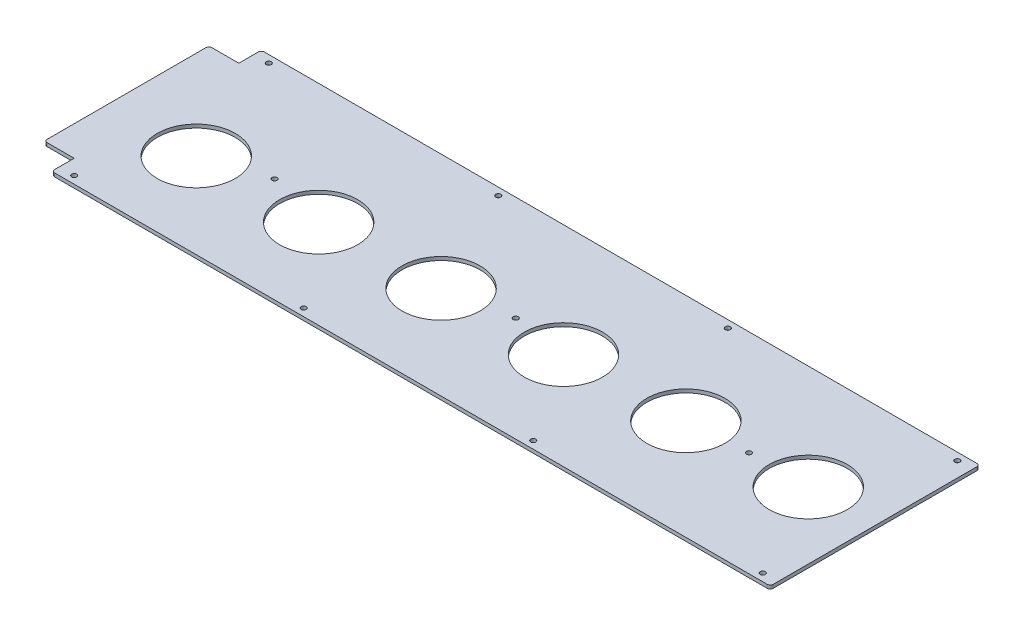
SolidWorks part; units mm, degrees
material "Acrylic (Medium-high impact)"
ref_plane "Front" through (0, 0, 0) normal (0, 0, 1) x (1, 0, 0)
ref_plane "Top" through (0, 0, 0) normal (0, 1, 0) x (1, 0, 0)
ref_plane "Right" through (0, 0, 0) normal (1, 0, 0) x (0, 0, -1)
sketch "Sketch1" plane through (0, 0, 0) normal (0, 1, 0) x (1, 0, 0)
  line L0 (1355.9397, -43.6078) -> (720.9397, -43.6078) construction
  line L5 (1355.9397, 24.9722) -> (1355.9397, -112.1878) construction
  line L6 (720.9397, -112.1878) -> (720.9397, 24.9722) construction
  line L12 (1354.6697, -113.4578) -> (722.2097, -113.4578) construction
  line L13 (746.3397, 45.2922) -> (1355.9397, 45.2922) construction
  line L27 (720.9397, 26.2422) -> (720.9397, -113.4578)
  line L32 (746.3397, -132.5078) -> (1355.9397, -132.5078) construction
  line L44 (1355.9397, 45.2922) -> (1355.9397, -132.5078)
  line L45 (746.3397, 45.2922) -> (1355.9397, -132.5078) construction
  line L50 (746.3397, -132.5078) -> (1355.9397, 45.2922) construction
  line L53 (720.9397, -113.4578) -> (746.3397, -113.4578)
  line L54 (746.3397, -132.5078) -> (746.3397, -113.4578)
  line L58 (720.9397, 26.2422) -> (746.3397, 26.2422)
  line L59 (746.3397, 45.2922) -> (746.3397, 26.2422)
  line L60 (722.2097, 26.2422) -> (1354.6697, 26.2422) construction
  line L61 (1355.9397, -132.5078) -> (746.3397, -132.5078)
  line L62 (1355.9397, 45.2922) -> (746.3397, 45.2922)
  circle A0 centre (1299.3357, -43.6078) radius 33.147
  circle A1 centre (1198.754, -46.8777) radius 33.147
  circle A2 centre (1098.1723, -50.1476) radius 33.147
  circle A3 centre (997.5907, -53.4175) radius 33.147
  circle A4 centre (897.009, -56.6874) radius 33.147
  circle A5 centre (796.4273, -59.9573) radius 33.147
  circle A6 centre (1299.3357, -43.6078) radius 33.02 construction
  point P6 (1051.1397, -43.6078)
  dimension "D3" = 0.127
  dimension "D1" = 177.8
  dimension "D2" = 25.4
extrude "Boss-Extrude1" add sketch "Sketch1" along normal blind 2.9718
hole_wizard "#8 Clearance Hole1" positions "Sketch2" profile "Sketch3" hole size "#8" standard "ANSI Inch" end condition through all
sketch "Sketch2" plane through (0, 2.9718, 0) normal (0, 1, 0) x (1, 0, 0)
  point P0 (759.0397, 38.9422)
  point P3 (759.0397, -126.1578)
  point P6 (953.773, -126.1578)
  point P9 (953.773, 38.9422)
  point P12 (1148.5063, 38.9422)
  point P15 (1148.5063, -126.1578)
  point P18 (1343.2397, -126.1578)
  point P22 (1343.2397, 38.9422)
  point P26 (1249.0183, -43.6078)
  point P29 (1051.1397, -43.6078)
  point P32 (846.4791, -43.6078)
sketch "Sketch3" plane through (759.0397, 2.9718, -38.9422) normal (1, 0, 0) x (0, 0, 1)
  line L0 (0, 0) -> (0, 2.9718)
  line L1 (0, 2.9718) -> (2.1526, 2.9718)
  line L2 (2.1526, 2.9718) -> (2.1526, 0)
  line L5 (2.1526, 0) -> (0, 0)
  line L11 (0, -6.35) -> (0, 107.95) construction
  dimension "Thru Hole Dia." = 4.3053
  dimension "Thru Hole Depth" = 2.9718
fillet "Fillet1" radius 2.54 6 edges at (720.9397, 1.4859, 113.4578) (720.9397, 1.4859, -26.2422) (746.3397, 1.4859, -45.2922) (746.3397, 1.4859, 132.5078) (1355.9397, 1.4859, 132.5078) (1355.9397, 1.4859, -45.2922)
